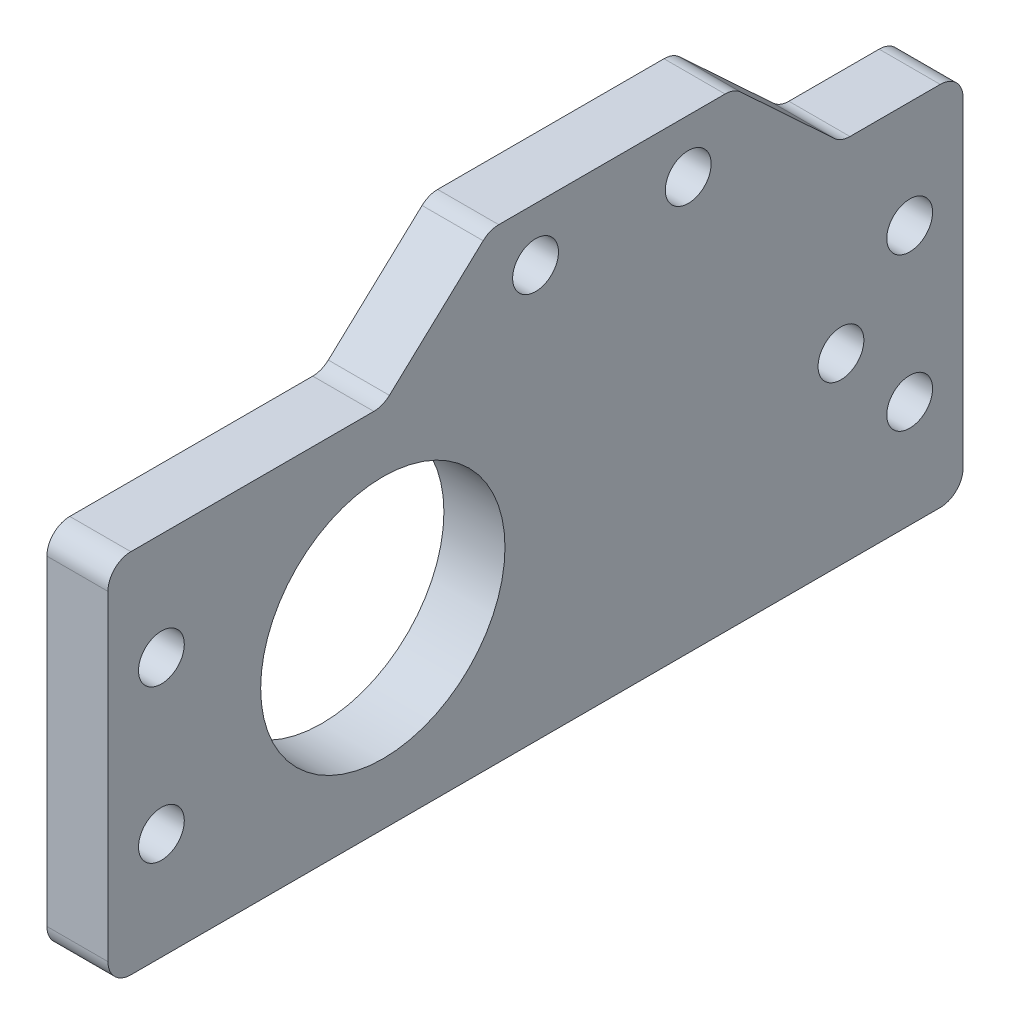
SolidWorks part; units mm, degrees
ref_plane "前视基准面" through (0, 0, 0) normal (0, 0, 1) x (1, 0, 0)
ref_plane "上视基准面" through (0, 0, 0) normal (0, 1, 0) x (1, 0, 0)
ref_plane "右视基准面" through (0, 0, 0) normal (1, 0, 0) x (0, 0, -1)
sketch "草图1" plane through (0, 0, 0) normal (1, 0, 0) x (0, 0, -1)
  line L0 (20.589, 12) -> (26.5, 12)
  line L1 (28, -10.5) -> (28, 10.5)
  line L2 (-26.5, -12) -> (26.5, -12)
  line L3 (-28, -10.5) -> (-28, 10.5)
  line L4 (-26.5, 12) -> (-10.589, 12)
  line L5 (-3.4316, 18.0992) -> (-9.5684, 12.4008)
  line L6 (-2.411, 18.5) -> (12.411, 18.5)
  line L7 (13.4316, 18.0992) -> (19.5684, 12.4008)
  circle A0 centre (0, 15) radius 1.5
  circle A1 centre (20, 0) radius 1.5
  circle A2 centre (-10, 0) radius 8
  circle A3 centre (24.5, 5) radius 1.5
  circle A4 centre (24.5, -5) radius 1.5
  circle A5 centre (-24.5, 5) radius 1.5
  circle A6 centre (-24.5, -5) radius 1.5
  circle A7 centre (10, 15) radius 1.5
  arc A8 (19.5684, 12.4008) -> (20.589, 12) centre (20.589, 13.5) ccw
  arc A9 (28, 10.5) -> (26.5, 12) centre (26.5, 10.5) ccw
  arc A10 (26.5, -12) -> (28, -10.5) centre (26.5, -10.5) ccw
  arc A11 (-28, -10.5) -> (-26.5, -12) centre (-26.5, -10.5) ccw
  arc A12 (-26.5, 12) -> (-28, 10.5) centre (-26.5, 10.5) ccw
  arc A13 (-10.589, 12) -> (-9.5684, 12.4008) centre (-10.589, 13.5) ccw
  arc A14 (-2.411, 18.5) -> (-3.4316, 18.0992) centre (-2.411, 17) ccw
  arc A15 (13.4316, 18.0992) -> (12.411, 18.5) centre (12.411, 17) ccw
extrude "凸台-拉伸1" add sketch "草图1" along normal blind 4
